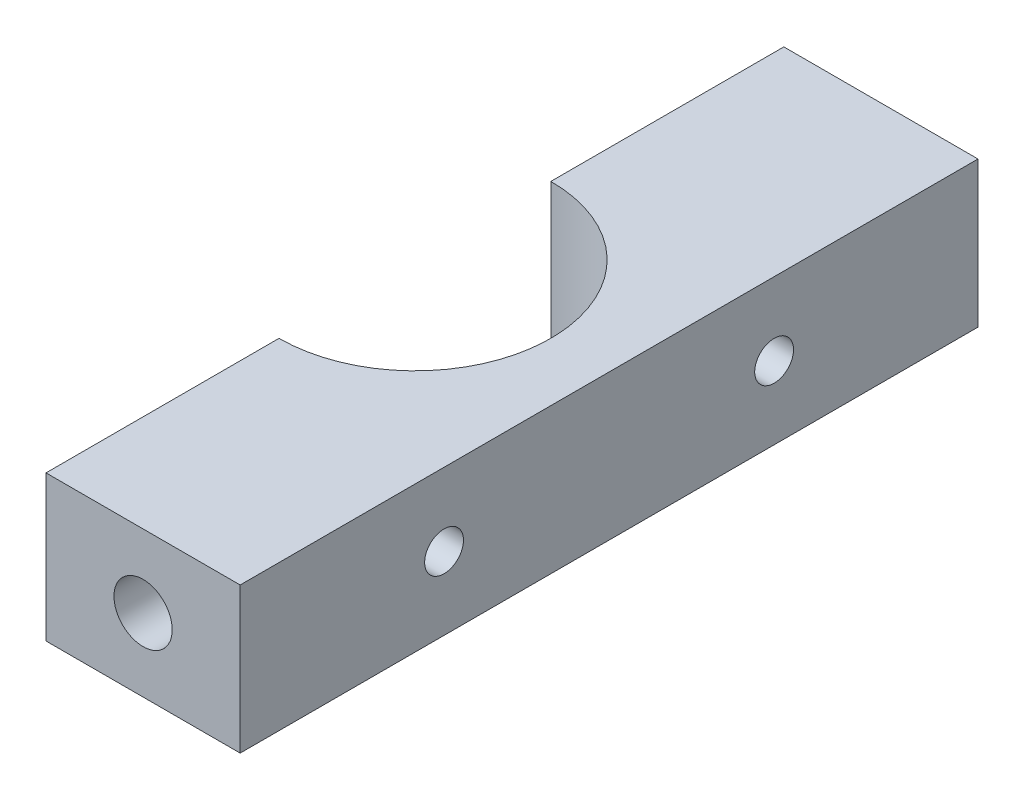
SolidWorks part; units mm, degrees
ref_plane "Спереди" through (0, 0, 0) normal (0, 0, 1) x (1, 0, 0)
ref_plane "Сверху" through (0, 0, 0) normal (0, 1, 0) x (1, 0, 0)
ref_plane "Справа" through (0, 0, 0) normal (1, 0, 0) x (0, 0, -1)
sketch "Эскиз1" plane through (0, 0, 0) normal (0, 1, 0) x (1, 0, 0)
  line L0 (0, -9.1978) -> (0, -3.5515) construction
  line L1 (0, -14) -> (0, -38)
  line L2 (0, -38) -> (20.0001, -38)
  line L3 (20.0001, -38) -> (20.0001, 38)
  line L4 (20.0001, 38) -> (0, 38)
  line L5 (0, 38) -> (0, 14)
  arc A0 (0, -14) -> (0, 14) centre (0, 0) ccw
extrude "Вытянуть1" add sketch "Эскиз1" along normal blind 15
sketch "Эскиз3" plane through (20.0001, 0, 0) normal (1, 0, 0) x (0, 0, -1)
  line L1 (-38, 15) -> (38, 15) construction
  line L2 (0, 0) -> (0, -17.9033) construction
  circle A0 centre (-17, 7.5) radius 2
  circle A1 centre (17, 7.5) radius 2
  dimension "D1" = 4
  dimension "D3" = 7.5
extrude "Вырез-Вытянуть3" cut sketch "Эскиз3" against normal mid plane 122
sketch "Эскиз5" plane through (0, 0, 38) normal (0, 0, 1) x (1, 0, 0)
  circle A0 centre (10, 7.5) radius 3
  dimension "D1" = 6
extrude "Вырез-Вытянуть4" cut sketch "Эскиз5" against normal blind 17
sketch "Эскиз6" plane through (0, 0, -38) normal (0, 0, 1) x (1, 0, 0)
  circle A0 centre (10, 7.5) radius 3
extrude "Вырез-Вытянуть5" cut sketch "Эскиз6" along normal blind 17
